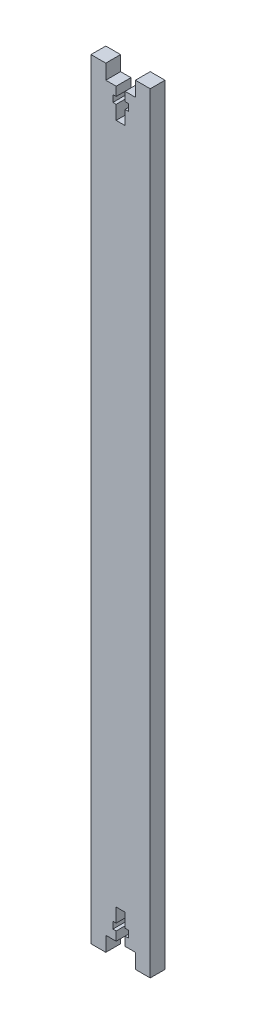
SolidWorks part; units mm, degrees
ref_plane "Front Plane" through (0, 0, 0) normal (0, 0, 1) x (1, 0, 0)
ref_plane "Top Plane" through (0, 0, 0) normal (0, 1, 0) x (1, 0, 0)
ref_plane "Right Plane" through (0, 0, 0) normal (1, 0, 0) x (0, 0, -1)
sketch "Sketch1" plane through (0, 0, 0) normal (0, 0, 1) x (1, 0, 0)
  line L6 (-10.1019, 9) -> (-10.1019, 16.2208) construction
  line L7 (-11.6019, 9) -> (-15.1019, 9)
  line L8 (-15.1019, 4) -> (-20.1019, 4)
  line L9 (-20.1019, 4) -> (-20.1019, 9)
  line L10 (-15.1019, 4) -> (-15.1019, 9)
  line L11 (-8.6019, 9) -> (-5.1019, 9)
  line L12 (-5.1019, 9) -> (-5.1019, 4)
  line L13 (-5.1019, 4) -> (-0.1019, 4)
  line L14 (-0.1019, 4) -> (-0.1019, 9)
  line L15 (-10.1019, 259) -> (-10.1019, 247.7792) construction
  line L16 (-8.6019, 259) -> (-5.1019, 259)
  line L17 (-5.1019, 264) -> (-0.1019, 264)
  line L18 (-0.1019, 264) -> (-0.1019, 259)
  line L19 (-5.1019, 264) -> (-5.1019, 259)
  line L20 (-11.6019, 259) -> (-15.1019, 259)
  line L21 (-15.1019, 259) -> (-15.1019, 264)
  line L22 (-15.1019, 264) -> (-20.1019, 264)
  line L23 (-20.1019, 264) -> (-20.1019, 259)
  line L24 (-8.6019, 259) -> (-11.6019, 259) construction
  line L25 (-11.6019, 259) -> (-11.6019, 256)
  line L26 (-11.6019, 253.7) -> (-12.7019, 253.7)
  line L27 (-7.5019, 256) -> (-7.5019, 253.7)
  line L28 (-12.7019, 256) -> (-11.6019, 256)
  line L29 (-11.6019, 253.7) -> (-11.6019, 249)
  line L30 (-11.6019, 249) -> (-8.6019, 249)
  line L31 (-8.6019, 249) -> (-8.6019, 253.7)
  line L32 (-8.6019, 256) -> (-7.5019, 256)
  line L33 (-12.7019, 253.7) -> (-12.7019, 256)
  line L34 (-7.5019, 253.7) -> (-8.6019, 253.7)
  line L35 (-8.6019, 256) -> (-8.6019, 259)
  line L36 (-10.1019, 249) -> (-10.1019, 259) construction
  line L37 (-11.6019, 9) -> (-8.6019, 9) construction
  line L38 (-8.6019, 9) -> (-8.6019, 12)
  line L39 (-8.6019, 14.3) -> (-7.5019, 14.3)
  line L40 (-12.7019, 12) -> (-12.7019, 14.3)
  line L41 (-7.5019, 12) -> (-8.6019, 12)
  line L42 (-8.6019, 14.3) -> (-8.6019, 19)
  line L43 (-8.6019, 19) -> (-11.6019, 19)
  line L44 (-11.6019, 19) -> (-11.6019, 14.3)
  line L45 (-11.6019, 12) -> (-12.7019, 12)
  line L46 (-7.5019, 14.3) -> (-7.5019, 12)
  line L47 (-12.7019, 14.3) -> (-11.6019, 14.3)
  line L48 (-11.6019, 12) -> (-11.6019, 9)
  line L49 (-10.1019, 19) -> (-10.1019, 9) construction
  line L50 (-1418.0935, 132) -> (-1348.6644, 132) construction
  line L51 (-20.1019, 259) -> (-20.1019, 9)
  line L52 (-0.1019, 259) -> (-0.1019, 9) construction
  line L53 (-47.476, 132) -> (32.9696, 132) construction
  line L54 (-19.1019, 138.4079) -> (-19.1019, 123.191) construction
  line L55 (-1.1019, 138.4079) -> (-1.1019, 123.191) construction
  line L56 (-0.1019, 9) -> (-0.1019, 259)
  dimension "D1" = 10
  dimension "D2" = 5
  dimension "D3" = 5
  dimension "D4" = 10
  dimension "D5" = 5
  dimension "D6" = 5
  dimension "D7" = 5.2
  dimension "D8" = 3
  dimension "D9" = 2.3
  dimension "D10" = 3
  dimension "D11" = 10
  dimension "D12" = 5.2
  dimension "D13" = 3
  dimension "D14" = 2.3
  dimension "D15" = 3
  dimension "D16" = 10
  dimension "D17" = 250
extrude "Boss-Extrude1" add sketch "Sketch1" along normal blind 5
sketch "Sketch2" plane through (0, 0, 5) normal (0, 0, 1) x (1, 0, 0)
  line L0 (-9.9476, 274.152) -> (-9.9476, -26.6804) construction
sketch "Sketch3" plane through (0, 0, 5) normal (0, 0, 1) x (1, 0, 0)
  line L0 (-9.9476, 274.152) -> (-9.9476, -26.6804) construction
  line L1 (-4.9476, 224) -> (-14.9476, 224)
  line L2 (-4.9476, 224) -> (-4.9476, 229)
  line L3 (-4.9476, 229) -> (-14.9476, 229)
  line L4 (-14.9476, 224) -> (-14.9476, 229)
  line L5 (-11.6019, 259) -> (-15.1019, 259) construction
  line L6 (-4.9476, 164) -> (-14.9476, 164)
  line L7 (-4.9476, 164) -> (-4.9476, 169)
  line L8 (-4.9476, 169) -> (-14.9476, 169)
  line L9 (-14.9476, 164) -> (-14.9476, 169)
  line L10 (-4.9476, 104) -> (-14.9476, 104)
  line L11 (-4.9476, 104) -> (-4.9476, 109)
  line L12 (-4.9476, 109) -> (-14.9476, 109)
  line L13 (-14.9476, 104) -> (-14.9476, 109)
  line L14 (-4.9476, 44) -> (-14.9476, 44)
  line L15 (-4.9476, 44) -> (-4.9476, 49)
  line L16 (-4.9476, 49) -> (-14.9476, 49)
  line L17 (-14.9476, 44) -> (-14.9476, 49)
  line L18 (-4.9476, 224) -> (-4.9476, 164) construction
  point P4 (-9.9476, 229)
  dimension "D1" = 10
  dimension "D2" = 5
  dimension "D3" = 30
  dimension "D5" = 60
  dimension "D4" = 4
extrude "Cut-Extrude1" [suppressed] cut sketch "Sketch3" against normal blind 5
